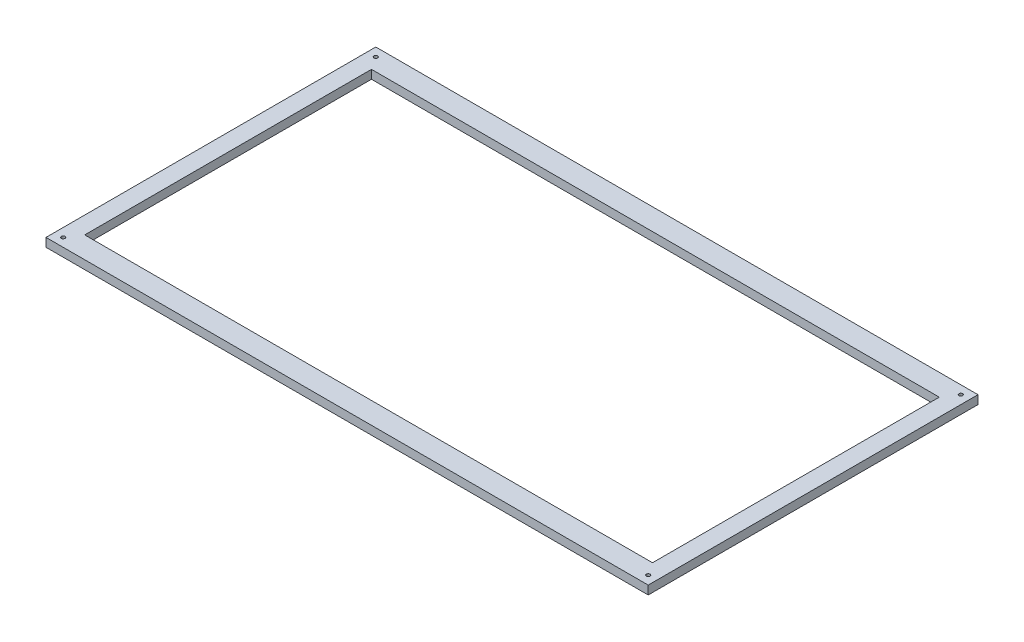
SolidWorks part; units mm, degrees
ref_plane "Front Plane" through (0, 0, 0) normal (0, 0, 1) x (1, 0, 0)
ref_plane "Top Plane" through (0, 0, 0) normal (0, 1, 0) x (1, 0, 0)
ref_plane "Right Plane" through (0, 0, 0) normal (1, 0, 0) x (0, 0, -1)
sketch "Sketch1" plane through (0, 0, 0) normal (0, 1, 0) x (1, 0, 0)
  line L0 (-1050, 575) -> (1050, 575)
  line L1 (1050, 575) -> (1050, -575)
  line L2 (-1050, 575) -> (-1050, -575)
  line L3 (-1050, -575) -> (1050, -575)
  line L4 (-990, 500) -> (990, 500)
  line L5 (990, 500) -> (990, -500)
  line L6 (990, -500) -> (-990, -500)
  line L7 (-990, -500) -> (-990, 500)
  line L8 (0, 500) -> (0, -500) construction
  line L9 (-990, 0) -> (990, 0) construction
  dimension "D1" = 2100
  dimension "D2" = 1150
  dimension "D3" = 60
  dimension "D4" = 60
  dimension "D5" = 75
  dimension "D6" = 75
extrude "Boss-Extrude1" add sketch "Sketch1" against normal blind 30
sketch "Sketch2" plane through (0, 0, 0) normal (0, 1, 0) x (1, 0, 0)
  line L0 (0, 575) -> (0, -575) construction
  line L1 (1050, 575) -> (-1050, 575) construction
  line L2 (-1050, -575) -> (1050, -575) construction
  line L3 (-1050, 0) -> (1050, 0) construction
  line L4 (-1050, 575) -> (-1050, -575) construction
  line L5 (1050, -575) -> (1050, 575) construction
  circle A0 centre (-1020, 545) radius 6.35
  circle A1 centre (-1020, -545) radius 6.35
  circle A2 centre (1020, 545) radius 6.35
  circle A3 centre (1020, -545) radius 6.35
  point P14 (0, 0)
  point P18 (-1020, 545)
  point P19 (0, 0)
  point P22 (0, 0)
  dimension "D1" = 12.7
  dimension "D2" = 30
  dimension "D3" = 30
extrude "Cut-Extrude1" cut sketch "Sketch2" against normal through all from surface at 0 starting at face at (0, 0, 0)
